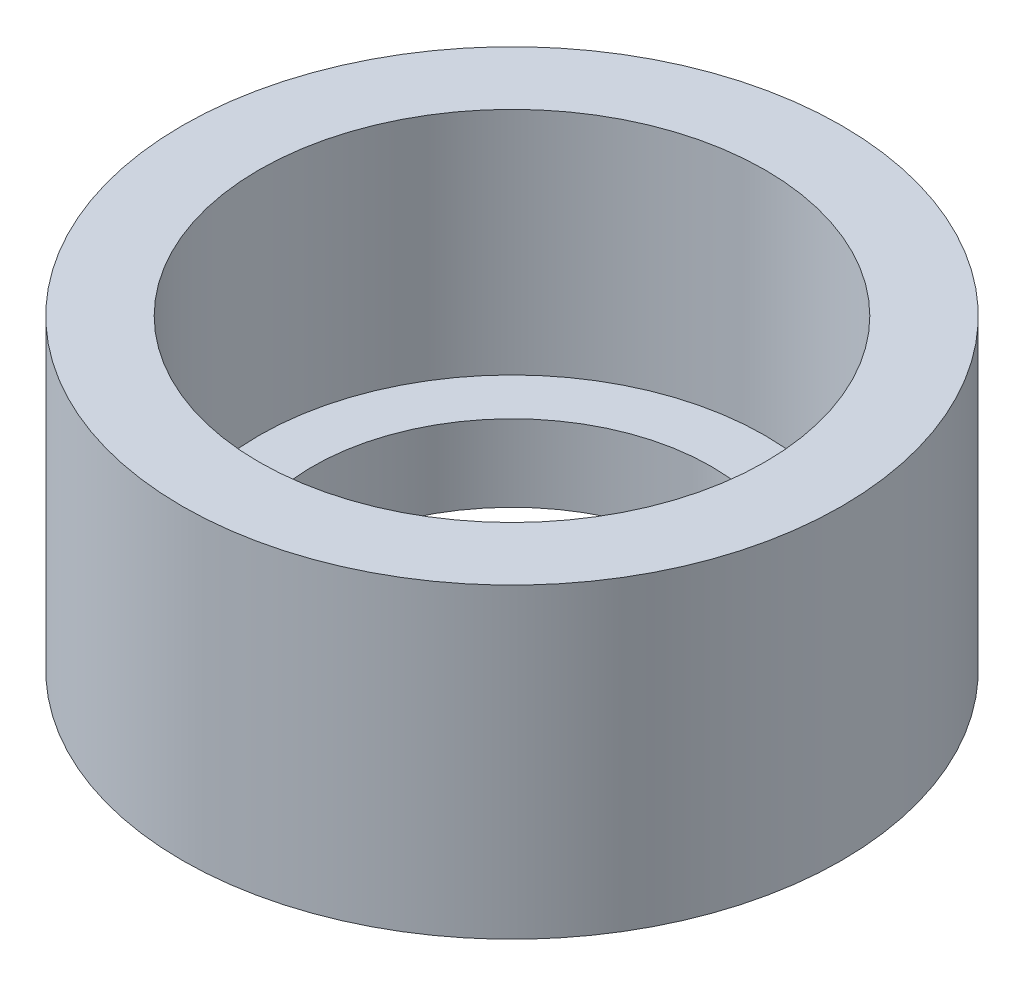
SolidWorks part; units mm, degrees
ref_plane "Front Plane" through (0, 0, 0) normal (0, 0, 1) x (1, 0, 0)
ref_plane "Top Plane" through (0, 0, 0) normal (0, 1, 0) x (1, 0, 0)
ref_plane "Right Plane" through (0, 0, 0) normal (1, 0, 0) x (0, 0, -1)
sketch "Sketch1" plane through (0, 0, 0) normal (0, 0, 1) x (1, 0, 0)
  line L0 (0, 0) -> (0, 5.3669)
  line L1 (2.6, 0) -> (4.3, 0)
  line L2 (2.6, 0) -> (2.6, 1)
  line L3 (2.6, 1) -> (4.3, 1)
  line L4 (4.3, 0) -> (4.3, 1)
  line L5 (4.3, 1) -> (3.3, 1)
  line L6 (4.3, 1) -> (4.3, 4)
  line L7 (4.3, 4) -> (3.3, 4)
  line L8 (3.3, 1) -> (3.3, 4)
revolve "Revolve2" add sketch "Sketch1" angle 360 about L0
